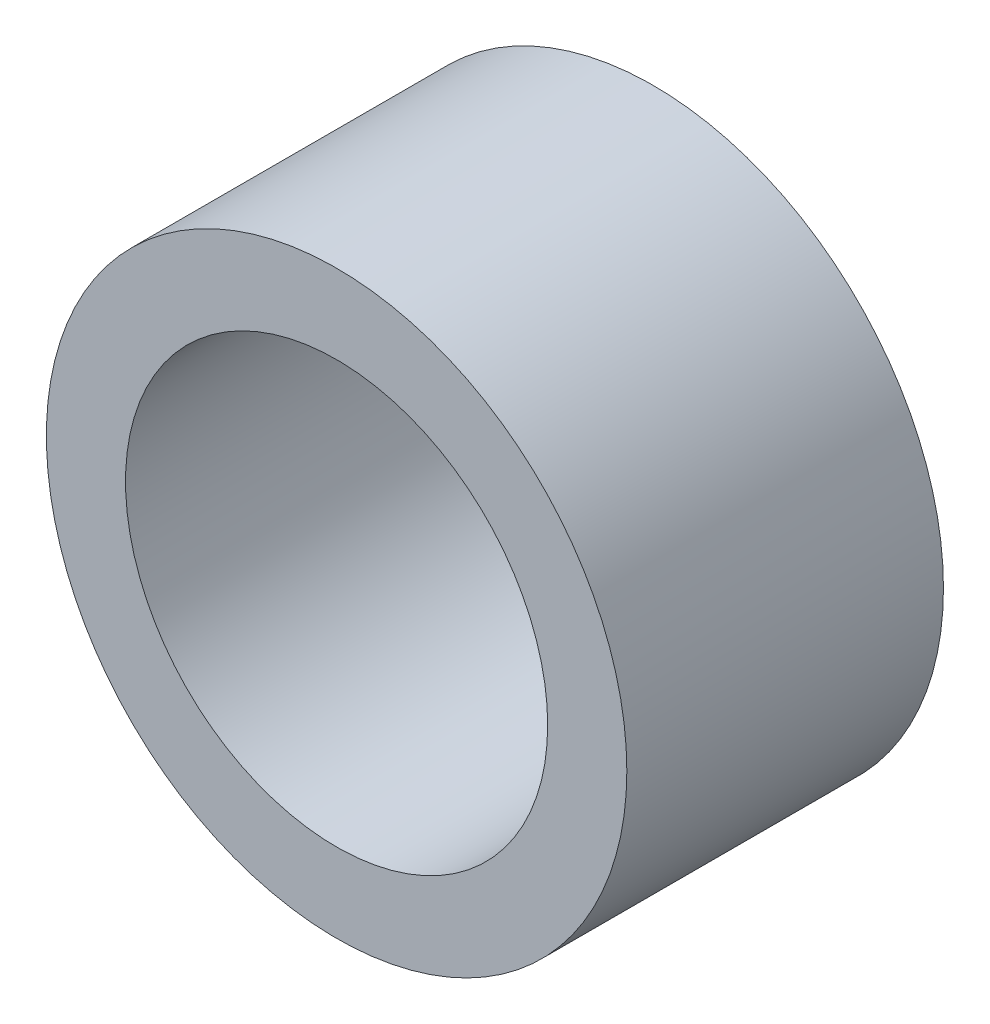
SolidWorks part; units mm, degrees
ref_plane "Front Plane" through (0, 0, 0) normal (0, 0, 1) x (1, 0, 0)
ref_plane "Top Plane" through (0, 0, 0) normal (0, 1, 0) x (1, 0, 0)
ref_plane "Right Plane" through (0, 0, 0) normal (1, 0, 0) x (0, 0, -1)
sketch "Sketch1" plane through (0, 0, 0) normal (0, 0, 1) x (1, 0, 0)
  circle A0 centre (0, 0) radius 11
  circle A1 centre (0, 0) radius 8
  dimension "D1" = 16
  dimension "D2" = 22
extrude "Boss-Extrude1" add sketch "Sketch1" along normal blind 12
